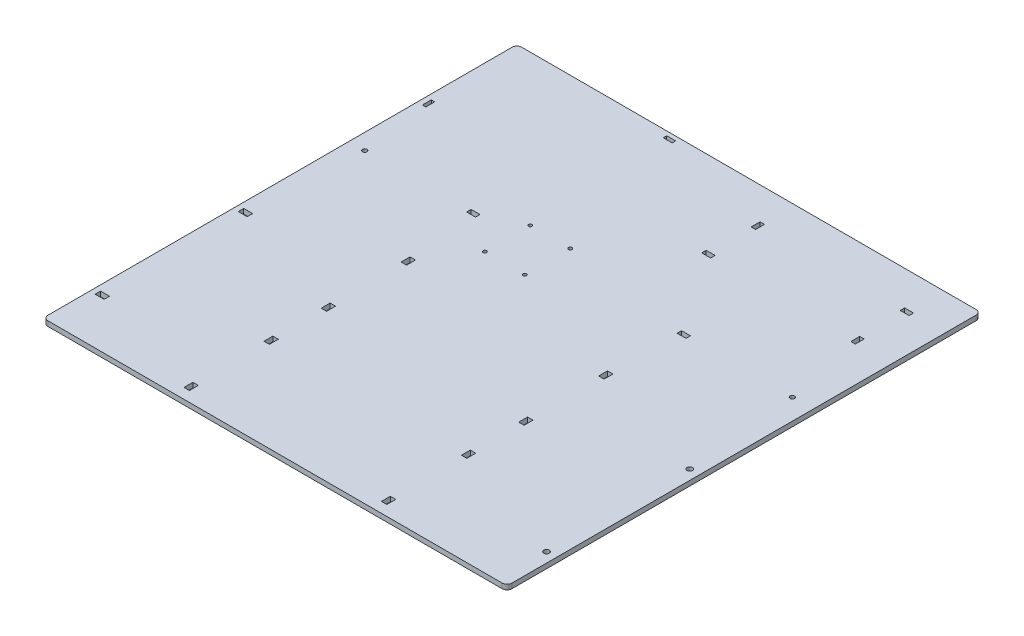
SolidWorks part; units mm, degrees
ref_plane "前视基准面" through (0, 0, 0) normal (0, 0, 1) x (1, 0, 0)
ref_plane "上视基准面" through (0, 0, 0) normal (0, 1, 0) x (1, 0, 0)
ref_plane "右视基准面" through (0, 0, 0) normal (1, 0, 0) x (0, 0, -1)
sketch "草图1" plane through (0, 0, 0) normal (0, 1, 0) x (1, 0, 0)
  line L1 (-235, -240) -> (235, -240)
  line L2 (-235, -240) -> (-235, 240)
  line L3 (-235, 240) -> (235, 240)
  line L4 (235, -240) -> (235, 240)
  line L5 (0, 240) -> (0, -240) construction
  line L6 (-235, 0) -> (235, 0) construction
  point P0 (0, 0)
  dimension "D1" = 470
  dimension "D2" = 480
extrude "凸台-拉伸1" add sketch "草图1" along normal blind 5
fillet "圆角1" radius 5 4 edges at (235, 2.5, -240) (-235, 2.5, -240) (-235, 2.5, 240) (235, 2.5, 240)
sketch "草图2" plane through (0, 5, 0) normal (0, 1, 0) x (1, 0, 0)
  line L0 (235, -235) -> (235, 235) construction
  line L1 (230, 240) -> (-230, 240) construction
  line L2 (-235, 235) -> (-235, -235) construction
  line L3 (-230, -240) -> (230, -240) construction
  line L4 (0, -278.1377) -> (0, 299.2239) construction
  circle A0 centre (197, 153) radius 2.25
  circle A1 centre (46, 153) radius 2.25
  circle A2 centre (197, 203) radius 2.25
  circle A3 centre (46, 203) radius 2.25
  circle A4 centre (-228, 143.5) radius 1.75
  circle A5 centre (-74.5, 234) radius 1.75
  circle A6 centre (-219, 69.8) radius 2.25
  circle A7 centre (-109, 69.8) radius 2.25
  circle A8 centre (-69.5, 42) radius 1.75
  circle A9 centre (-69.5, 88) radius 1.75
  circle A10 centre (-29, 42) radius 1.75
  circle A11 centre (-29, 88) radius 1.75
  circle A12 centre (214, 70) radius 2.25
  circle A13 centre (104, 70) radius 2.25
  circle A14 centre (225, -190) radius 2.75
  circle A15 centre (225, -45) radius 2.75
  circle A16 centre (100, -5) radius 2.75
  circle A17 centre (100, -225) radius 2.75
  circle A18 centre (100, -144) radius 2.75
  circle A19 centre (100, -86) radius 2.75
  circle A20 centre (-100, -5) radius 2.75
  circle A21 centre (-100, -86) radius 2.75
  circle A22 centre (-100, -144) radius 2.75
  circle A23 centre (-100, -225) radius 2.75
  circle A24 centre (-225, -45) radius 2.75
  circle A25 centre (-225, -190) radius 2.75
  dimension "D3" = 4.5
  dimension "D6" = 4.5
  dimension "D9" = 4.5
  dimension "D12" = 4.5
  dimension "D14" = 3.5
  dimension "D17" = 3.5
  dimension "D20" = 4.5
  dimension "D23" = 4.5
  dimension "D26" = 3.5
  dimension "D28" = 3.5
  dimension "D30" = 3.5
  dimension "D33" = 3.5
  dimension "D36" = 4.5
  dimension "D38" = 4.5
  dimension "D41" = 5.5
  dimension "D44" = 5.5
  dimension "D47" = 5.5
  dimension "D50" = 5.5
  dimension "D53" = 5.5
  dimension "D54" = 5.5
  dimension "D1" = 38
  dimension "D2" = 87
  dimension "D4" = 87
  dimension "D7" = 38
  dimension "D8" = 37
  dimension "D10" = 151
  dimension "D11" = 37
  dimension "D13" = 7
  dimension "38.5" = 96.5
  dimension "D15" = 160.5
  dimension "D16" = 6
  dimension "D18" = 16
  dimension "D19" = 170.2
  dimension "D21" = 110
  dimension "D22" = 170.2
  dimension "D24" = 165.5
  dimension "D25" = 198
  dimension "D27" = 46
  dimension "D29" = 40.5
  dimension "D31" = 40.5
  dimension "D32" = 46
  dimension "D34" = 21
  dimension "D35" = 170
  dimension "D37" = 110
  dimension "D39" = 50
  dimension "D40" = 10
  dimension "D42" = 195
  dimension "D43" = 10
  dimension "D45" = 135
  dimension "D46" = 235
  dimension "D48" = 15
  dimension "D49" = 135
  dimension "D51" = 96
  dimension "D52" = 154
  dimension "D55" = 151
extrude "切除-拉伸1" cut sketch "草图2" against normal through all
sketch "草图3" plane through (0, 5, 0) normal (0, 1, 0) x (1, 0, 0)
  line L0 (0, 36.2852) -> (0, -272.151) construction
  line L1 (108.5, 72.25) -> (99.5, 72.25)
  line L2 (108.5, 72.25) -> (108.5, 67.75)
  line L3 (108.5, 67.75) -> (99.5, 67.75)
  line L4 (99.5, 72.25) -> (99.5, 67.75)
  line L5 (104, 67.75) -> (104, 72.25) construction
  line L6 (108.5, 70) -> (99.5, 70) construction
  line L7 (-104.5, 72.05) -> (-113.5, 72.05)
  line L8 (-104.5, 72.05) -> (-104.5, 67.55)
  line L9 (-104.5, 67.55) -> (-113.5, 67.55)
  line L10 (-113.5, 72.05) -> (-113.5, 67.55)
  line L11 (-109, 67.55) -> (-109, 72.05) construction
  line L12 (-104.5, 69.8) -> (-113.5, 69.8) construction
  line L13 (199.25, 157.5) -> (194.75, 157.5)
  line L14 (199.25, 157.5) -> (199.25, 148.5)
  line L15 (199.25, 148.5) -> (194.75, 148.5)
  line L16 (194.75, 157.5) -> (194.75, 148.5)
  line L17 (197, 148.5) -> (197, 157.5) construction
  line L18 (199.25, 153) -> (194.75, 153) construction
  line L19 (-70, 235.75) -> (-79, 235.75)
  line L20 (-70, 235.75) -> (-70, 232.25)
  line L21 (-70, 232.25) -> (-79, 232.25)
  line L22 (-79, 235.75) -> (-79, 232.25)
  line L23 (-74.5, 232.25) -> (-74.5, 235.75) construction
  line L24 (-70, 234) -> (-79, 234) construction
  line L25 (-226.25, 148) -> (-229.75, 148)
  line L26 (-226.25, 148) -> (-226.25, 139)
  line L27 (-226.25, 139) -> (-229.75, 139)
  line L28 (-229.75, 148) -> (-229.75, 139)
  line L29 (-228, 139) -> (-228, 148) construction
  line L30 (-226.25, 143.5) -> (-229.75, 143.5) construction
  line L31 (201.5, 205.25) -> (192.5, 205.25)
  line L32 (201.5, 205.25) -> (201.5, 200.75)
  line L33 (201.5, 200.75) -> (192.5, 200.75)
  line L34 (192.5, 205.25) -> (192.5, 200.75)
  line L35 (197, 200.75) -> (197, 205.25) construction
  line L36 (201.5, 203) -> (192.5, 203) construction
  line L37 (48.25, 207.5) -> (43.75, 207.5)
  line L38 (48.25, 207.5) -> (48.25, 198.5)
  line L39 (48.25, 198.5) -> (43.75, 198.5)
  line L40 (43.75, 207.5) -> (43.75, 198.5)
  line L41 (46, 198.5) -> (46, 207.5) construction
  line L42 (48.25, 203) -> (43.75, 203) construction
  line L43 (50.5, 155.25) -> (41.5, 155.25)
  line L44 (50.5, 155.25) -> (50.5, 150.75)
  line L45 (50.5, 150.75) -> (41.5, 150.75)
  line L46 (41.5, 155.25) -> (41.5, 150.75)
  line L47 (46, 150.75) -> (46, 155.25) construction
  line L48 (50.5, 153) -> (41.5, 153) construction
  line L49 (102.75, -220.5) -> (97.25, -220.5)
  line L50 (102.75, -220.5) -> (102.75, -229.5)
  line L51 (102.75, -229.5) -> (97.25, -229.5)
  line L52 (97.25, -220.5) -> (97.25, -229.5)
  line L53 (100, -229.5) -> (100, -220.5) construction
  line L54 (102.75, -225) -> (97.25, -225) construction
  line L55 (102.75, -139.5) -> (97.25, -139.5)
  line L56 (102.75, -139.5) -> (102.75, -148.5)
  line L57 (102.75, -148.5) -> (97.25, -148.5)
  line L58 (97.25, -139.5) -> (97.25, -148.5)
  line L59 (100, -148.5) -> (100, -139.5) construction
  line L60 (102.75, -144) -> (97.25, -144) construction
  line L61 (102.75, -81.5) -> (97.25, -81.5)
  line L62 (102.75, -81.5) -> (102.75, -90.5)
  line L63 (102.75, -90.5) -> (97.25, -90.5)
  line L64 (97.25, -81.5) -> (97.25, -90.5)
  line L65 (100, -90.5) -> (100, -81.5) construction
  line L66 (102.75, -86) -> (97.25, -86) construction
  line L67 (102.75, -0.5) -> (97.25, -0.5)
  line L68 (102.75, -0.5) -> (102.75, -9.5)
  line L69 (102.75, -9.5) -> (97.25, -9.5)
  line L70 (97.25, -0.5) -> (97.25, -9.5)
  line L71 (100, -9.5) -> (100, -0.5) construction
  line L72 (102.75, -5) -> (97.25, -5) construction
  line L73 (-220.5, -187.25) -> (-229.5, -187.25)
  line L74 (-220.5, -187.25) -> (-220.5, -192.75)
  line L75 (-220.5, -192.75) -> (-229.5, -192.75)
  line L76 (-229.5, -187.25) -> (-229.5, -192.75)
  line L77 (-225, -192.75) -> (-225, -187.25) construction
  line L78 (-220.5, -190) -> (-229.5, -190) construction
  line L79 (-220.5, -42.25) -> (-229.5, -42.25)
  line L80 (-220.5, -42.25) -> (-220.5, -47.75)
  line L81 (-220.5, -47.75) -> (-229.5, -47.75)
  line L82 (-229.5, -42.25) -> (-229.5, -47.75)
  line L83 (-225, -47.75) -> (-225, -42.25) construction
  line L84 (-220.5, -45) -> (-229.5, -45) construction
  line L85 (-97.25, -0.5) -> (-97.25, -9.5)
  line L86 (-102.75, -0.5) -> (-97.25, -0.5)
  line L87 (-102.75, -0.5) -> (-102.75, -9.5)
  line L88 (-102.75, -9.5) -> (-97.25, -9.5)
  line L89 (-97.25, -81.5) -> (-97.25, -90.5)
  line L90 (-102.75, -81.5) -> (-97.25, -81.5)
  line L91 (-102.75, -81.5) -> (-102.75, -90.5)
  line L92 (-102.75, -90.5) -> (-97.25, -90.5)
  line L93 (-97.25, -139.5) -> (-97.25, -148.5)
  line L94 (-102.75, -139.5) -> (-97.25, -139.5)
  line L95 (-102.75, -139.5) -> (-102.75, -148.5)
  line L96 (-102.75, -148.5) -> (-97.25, -148.5)
  line L97 (-102.75, -220.5) -> (-97.25, -220.5)
  line L98 (-102.75, -220.5) -> (-102.75, -229.5)
  line L99 (-102.75, -229.5) -> (-97.25, -229.5)
  line L100 (-97.25, -220.5) -> (-97.25, -229.5)
  point P0 (104, 70)
  point P4 (-109, 69.8)
  point P8 (197, 153)
  point P12 (-74.5, 234)
  point P16 (-228, 143.5)
  point P20 (197, 203)
  point P24 (46, 203)
  point P28 (46, 153)
  point P32 (100, -225)
  point P36 (100, -144)
  point P40 (100, -86)
  point P44 (100, -5)
  point P48 (-225, -190)
  point P52 (-225, -45)
  dimension "D1" = 4.5
  dimension "D2" = 9
  dimension "D3" = 4.5
  dimension "D4" = 9
  dimension "D5" = 4.5
  dimension "D6" = 9
  dimension "D7" = 3.5
  dimension "D8" = 9
  dimension "D9" = 3.5
  dimension "D10" = 9
  dimension "D11" = 4.5
  dimension "D12" = 9
  dimension "D13" = 4.5
  dimension "D14" = 9
  dimension "D15" = 9
  dimension "D16" = 4.5
  dimension "D17" = 5.5
  dimension "D18" = 9
  dimension "D19" = 5.5
  dimension "D20" = 5.5
  dimension "D21" = 5.5
  dimension "D22" = 9
  dimension "D23" = 9
  dimension "D24" = 9
  dimension "D25" = 5.5
  dimension "D26" = 9
  dimension "D27" = 5.5
  dimension "D28" = 9
extrude "切除-拉伸2" cut sketch "草图3" against normal through all
